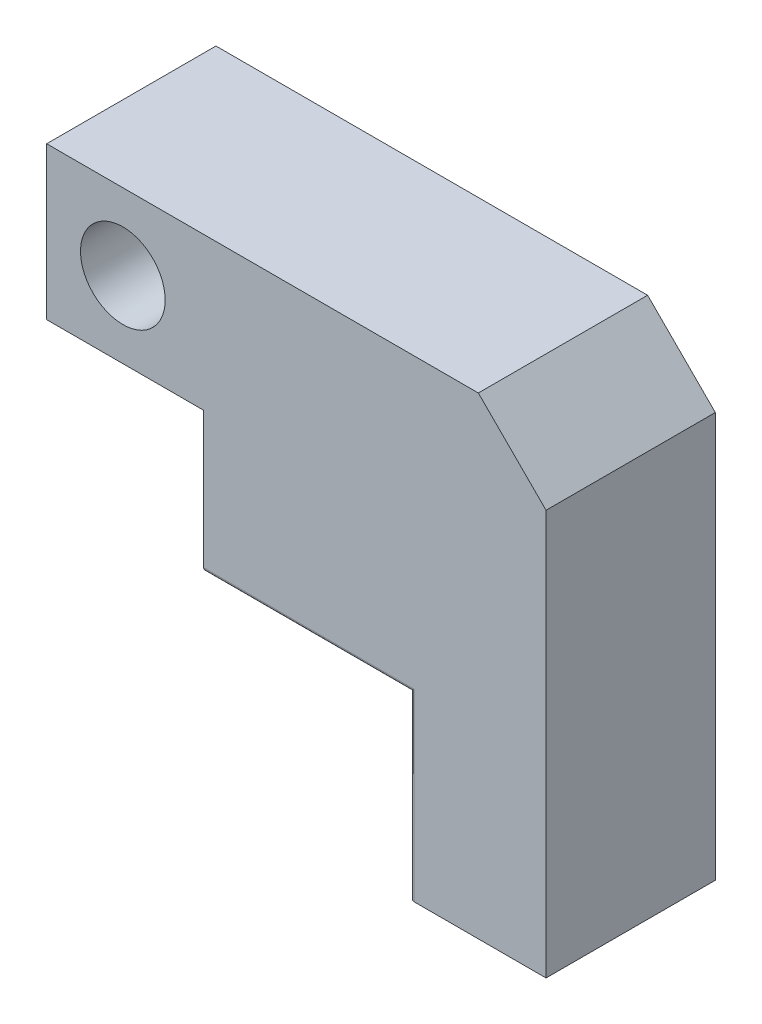
SolidWorks part; units mm, degrees
ref_plane "Спереди" through (0, 0, 0) normal (0, 0, 1) x (1, 0, 0)
ref_plane "Сверху" through (0, 0, 0) normal (0, 1, 0) x (1, 0, 0)
ref_plane "Справа" through (0, 0, 0) normal (1, 0, 0) x (0, 0, -1)
sketch "Эскиз1" plane through (0, 0, 0) normal (0, 0, 1) x (1, 0, 0)
  line L0 (17, -23.4294) -> (17, -12.7541)
  line L1 (-4.5, 4.5) -> (25, 4.5)
  line L2 (-4.5, 4.5) -> (-4.5, -4.5)
  line L3 (-4.5, -4.5) -> (4.7765, -4.5)
  line L4 (17, -23.4294) -> (25, -23.4294)
  line L5 (25, 4.5) -> (25, -23.4294)
  line L6 (4.7765, -4.5) -> (4.7765, -12.7541)
  line L7 (4.7765, -12.7541) -> (17, -12.7541)
  circle A0 centre (0, 0) radius 2.5
  dimension "D1" = 8
extrude "Вытянуть1" add sketch "Эскиз1" along normal blind 10
sketch "Эскиз2" plane through (0, -23.4294, 0) normal (0, -1, 0) x (1, 0, 0)
  circle A0 centre (21, 5) radius 2.5
extrude "Вырез-Вытянуть1" cut sketch "Эскиз2" against normal blind 20
chamfer "Фаска1" distance 4 angle 45 1 edges at (25, 4.5, 5)
fillet "Скругление1" radius 0.2 4 edges at (17, -18.0917, 10) (17, -18.0917, 0) (10.8883, -12.7541, 0) (10.8883, -12.7541, 10)
